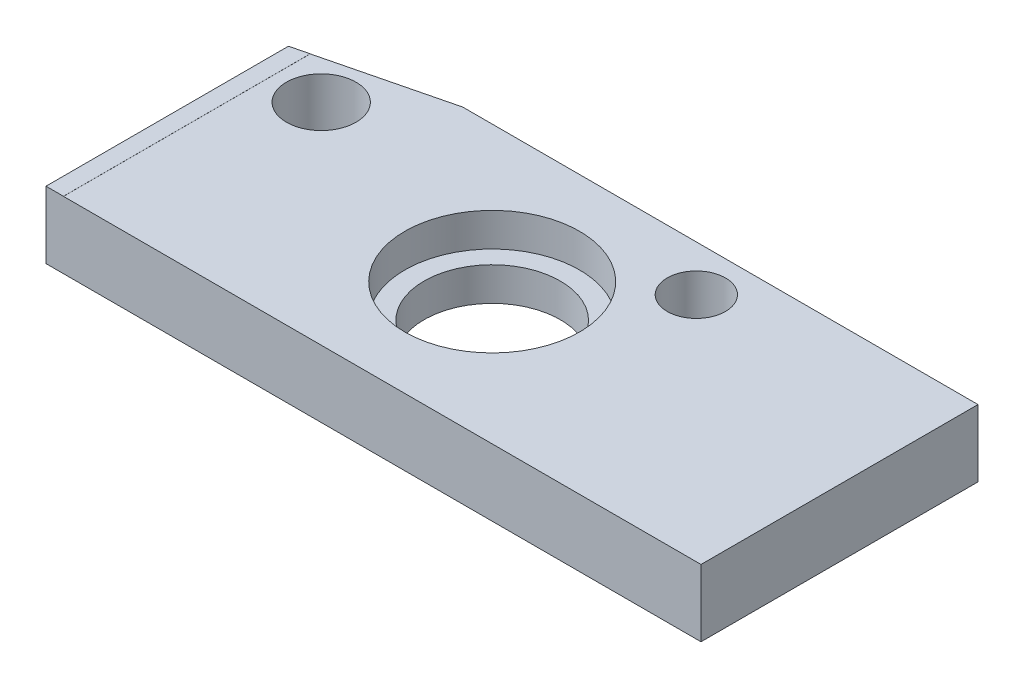
SolidWorks part; units mm, degrees
ref_plane "Front Plane" through (0, 0, 0) normal (0, 0, 1) x (1, 0, 0)
ref_plane "Top Plane" through (0, 0, 0) normal (0, 1, 0) x (1, 0, 0)
ref_plane "Right Plane" through (0, 0, 0) normal (1, 0, 0) x (0, 0, -1)
sketch "Sketch1" plane through (0, 0, 0) normal (0, 1, 0) x (1, 0, 0)
  line L1 (0, 0) -> (225.425, 0)
  line L3 (0, 100.6932) -> (225.425, 100.6932)
  line L4 (225.425, 0) -> (225.425, 100.6932)
  line L6 (0, 100.6932) -> (0, 0)
  dimension "D1" = 225.425
  dimension "D2" = 100.6932
extrude "Boss-Extrude1" add sketch "Sketch1" along normal blind 24.3535 contours L3 L4 L1 L6
ref_plane "Plane1" through (0, 0, -100.6932) normal (0, 0, 1) x (1, 0, 0)
sketch "Sketch2" plane through (0, 0, -100.6932) normal (0, 0, 1) x (1, 0, 0)
  line L1 (0, 0) -> (-6.35, 0)
  line L2 (0, 0) -> (0, 24.3854)
  line L3 (0, 24.3854) -> (-6.35, 24.3854)
  line L4 (-6.35, 0) -> (-6.35, 24.3854)
  dimension "D1" = 24.3854
  dimension "D2" = 6.35
extrude "Boss-Extrude2" add sketch "Sketch2" along normal blind 100.6932
ref_plane "Plane2" through (225.425, 0, -100.6932) normal (0, 0, -1) x (-1, 0, 0)
sketch "Sketch3" plane through (225.425, 0, -100.6932) normal (0, 0, -1) x (-1, 0, 0)
  line L1 (0, 0) -> (-6.35, 0)
  line L2 (0, 0) -> (0, 24.3535)
  line L3 (0, 24.3535) -> (-6.35, 24.3535)
  line L4 (-6.35, 0) -> (-6.35, 24.3535)
  dimension "D1" = 6.35
  dimension "D2" = 24.3535
extrude "Boss-Extrude3" add sketch "Sketch3" against normal blind 100.6932
sketch "Sketch4" plane through (0, 24.3535, 0) normal (0, 1, 0) x (1, 0, 0)
  line L0 (-6.35, 0) -> (-6.35, 100.6932) construction
  line L1 (0, 0) -> (231.775, 0) construction
  circle A0 centre (17.2085, 76.4972) radius 12.6454
  circle A1 centre (145.9967, 84.074) radius 10.5867
  dimension "D3" = 25.2908
  dimension "D5" = 21.1734
  dimension "D1" = 23.5585
  dimension "D2" = 76.4972
  dimension "D4" = 152.3467
  dimension "D6" = 84.074
extrude "Cut-Extrude1" cut sketch "Sketch4" against normal through all
sketch "Sketch5" plane through (0, 24.3854, 0) normal (0, 1, 0) x (1, 0, 0)
  line L0 (-6.35, 88.1397) -> (44.45, 100.6932)
  line L1 (-6.35, 0) -> (-6.35, 100.6932) construction
  line L2 (-55, 100.6932) -> (55, 100.6932) construction
  dimension "D1" = 76.119
  dimension "D2" = 50.8
extrude "Cut-Extrude2" cut sketch "Sketch5" against normal through all and the other way through all
sketch "Sketch16" plane through (0, 24.3535, 0) normal (0, 1, 0) x (1, 0, 0)
  line L0 (0, 0) -> (231.775, 0) construction
  line L1 (-6.35, 0) -> (-6.35, 88.1397) construction
  circle A0 centre (104.7826, 51.0794) radius 31.75
  circle A1 centre (104.7826, 51.0794) radius 24.765
  dimension "D3" = 63.5
  dimension "D4" = 49.53
  dimension "D1" = 51.0794
  dimension "D2" = 111.1326
extrude "Cut-Extrude6" cut sketch "Sketch16" against normal blind 12.1768
sketch "Sketch17" plane through (0, 24.3535, 0) normal (0, 1, 0) x (1, 0, 0)
  circle A0 centre (104.7826, 51.0794) radius 24.765
  dimension "D1" = 49.53
extrude "Cut-Extrude7" cut sketch "Sketch17" against normal through all
